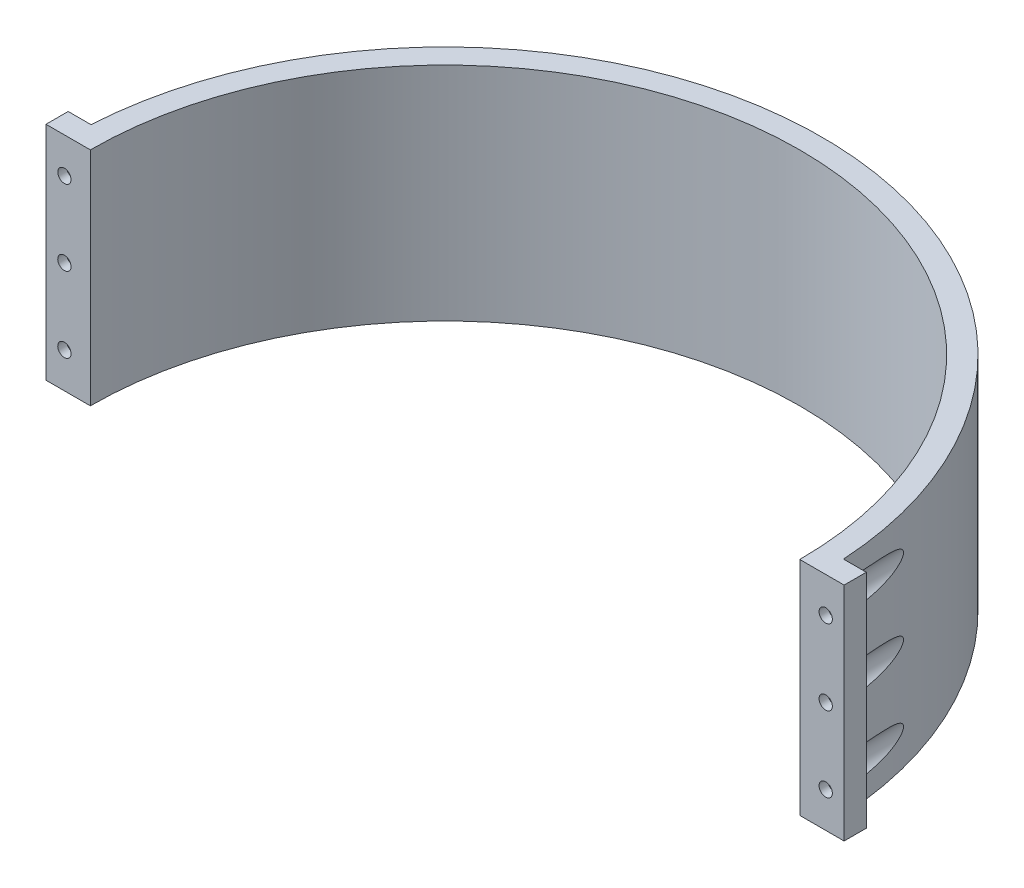
SolidWorks part; units mm, degrees
ref_plane "Front Plane" through (0, 0, 0) normal (0, 0, 1) x (1, 0, 0)
ref_plane "Top Plane" through (0, 0, 0) normal (0, 1, 0) x (1, 0, 0)
ref_plane "Right Plane" through (0, 0, 0) normal (1, 0, 0) x (0, 0, -1)
sketch "Sketch1" plane through (0, 0, 0) normal (0, 1, 0) x (1, 0, 0)
  line L0 (-85, 0) -> (-80, 0)
  line L1 (80, 0) -> (85, 0)
  arc A0 (80, 0) -> (-80, 0) centre (0, 0) ccw
  arc A1 (85, 0) -> (-85, 0) centre (0, 0) ccw
  circle A2 centre (0, 0) radius 85 construction
  circle A3 centre (0, 0) radius 80 construction
  dimension "D1" = 160
  dimension "D2" = 5
extrude "Boss-Extrude1" add sketch "Sketch1" along normal blind 50
sketch "Sketch2" plane through (0, 0, 0) normal (0, 0, 1) x (1, 0, 0)
  line L1 (90, 50) -> (85, 50)
  line L2 (90, 50) -> (90, 0)
  line L3 (90, 50) -> (90, 0)
  line L4 (85, 50) -> (85, 0)
  line L5 (85, 0) -> (90, 0)
  line L6 (0, -27.5) -> (0, 27.5) construction
  line L7 (-85, 0) -> (-90, 0)
  line L8 (-85, 50) -> (-85, 0)
  line L9 (-90, 50) -> (-85, 50)
  line L10 (-90, 50) -> (-90, 0)
  dimension "D1" = 5
extrude "Boss-Extrude2" add sketch "Sketch2" against normal blind 5 separate body
sketch "Sketch3" plane through (0, 50, 0) normal (0, 1, 0) x (1, 0, 0)
  line L0 (-90, 5) -> (-81.9049, 5)
  line L1 (-81.9049, 5) -> (-81.9049, 0)
  line L2 (-85, 0) -> (-80, 0) construction
  line L3 (-81.9049, 0) -> (-90, 0)
  line L4 (-90, 0) -> (-90, 5)
  line L5 (0, -27.5) -> (0, 27.5) construction
  line L6 (81.9049, 0) -> (90, 0)
  line L7 (81.9049, 5) -> (81.9049, 0)
  line L8 (90, 5) -> (81.9049, 5)
  line L9 (90, 0) -> (90, 5)
extrude "Boss-Extrude3" add sketch "Sketch3" against normal up to surface (50 mm away) up to face at (-87.5, 0, -2.5)
sketch "Sketch4" plane through (0, 0, -5) normal (0, 0, -1) x (-1, 0, 0)
  line L1 (0, 27.5) -> (0, -27.5) construction
  line L2 (85.8528, 0) -> (85.8528, 50)
  line L3 (85.8528, 0) -> (85.8528, 50) construction
  line L4 (-85.8528, 0) -> (-85.8528, 50) construction
  circle A0 centre (85.8528, 42) radius 3.5
  circle A1 centre (85.8528, 25) radius 3.5
  circle A2 centre (85.8528, 8) radius 3.5
  circle A3 centre (-85.8528, 8) radius 3.5
  circle A4 centre (-85.8528, 25) radius 3.5
  circle A5 centre (-85.8528, 42) radius 3.5
  dimension "D2" = 7
  dimension "D3" = 17
  dimension "D4" = 17
  dimension "D1" = 1
extrude "Cut-Extrude1" cut sketch "Sketch4" against normal blind 3 and the other way through all
sketch "Sketch5" plane through (0, 0, -2) normal (0, 0, -1) x (-1, 0, 0)
  line L0 (0, 27.5) -> (0, -27.5) construction
  circle A2 centre (85.8528, 42) radius 1.5
  circle A3 centre (85.8528, 42) radius 1.5
  circle A7 centre (85.8528, 25) radius 1.5
  circle A8 centre (85.8528, 25) radius 1.5
  circle A9 centre (-85.8528, 8) radius 1.5
  circle A10 centre (85.8528, 8) radius 1.5
  circle A11 centre (85.8528, 8) radius 1.5
  circle A12 centre (-85.8528, 25) radius 1.5
  circle A13 centre (-85.8528, 42) radius 1.5
  dimension "D1" = 2
  dimension "D2" = 2
  dimension "D3" = 2
extrude "Cut-Extrude2" cut sketch "Sketch5" against normal through all
